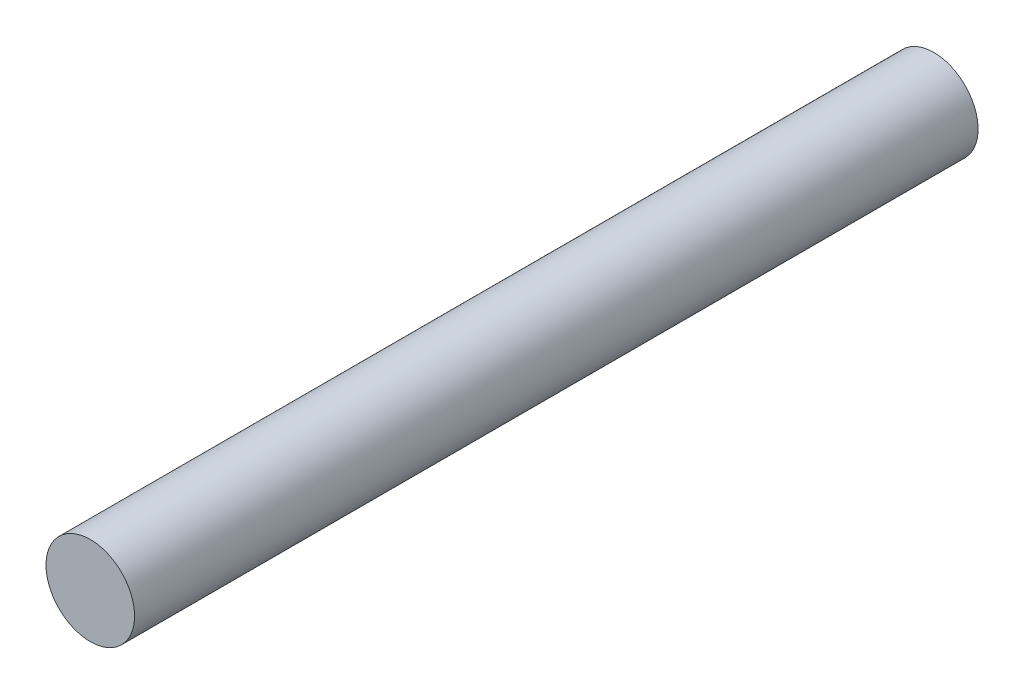
SolidWorks part; units mm, degrees
ref_plane "Plan de face" through (0, 0, 0) normal (0, 0, 1) x (1, 0, 0)
ref_plane "Plan de dessus" through (0, 0, 0) normal (0, 1, 0) x (1, 0, 0)
ref_plane "Plan de droite" through (0, 0, 0) normal (1, 0, 0) x (0, 0, -1)
sketch "Esquisse2" plane through (0, 0, 0) normal (0, 0, 1) x (1, 0, 0)
  circle A0 centre (0, 0) radius 2
  dimension "D1" = 4
extrude "Boss.-Extru.1" add sketch "Esquisse2" along normal mid plane 38.1
